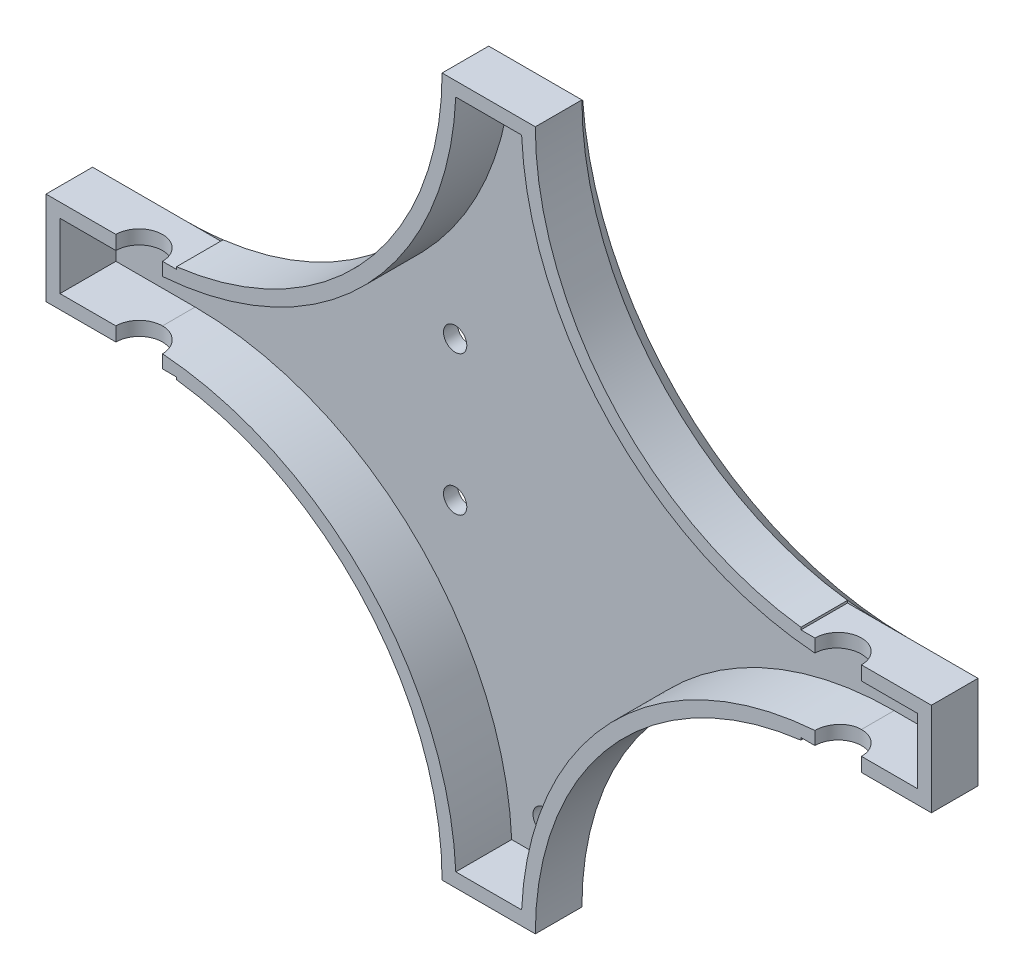
SolidWorks part; units mm, degrees
ref_plane "Front Plane" through (0, 0, 0) normal (0, 0, 1) x (1, 0, 0)
ref_plane "Top Plane" through (0, 0, 0) normal (0, 1, 0) x (1, 0, 0)
ref_plane "Right Plane" through (0, 0, 0) normal (1, 0, 0) x (0, 0, -1)
sketch "Sketch1" plane through (0, 0, 0) normal (0, 0, 1) x (1, 0, 0)
  line L1 (100, -75) -> (-100, -75)
  line L2 (100, -75) -> (100, 75)
  line L3 (100, 75) -> (-100, 75)
  line L4 (-100, -75) -> (-100, 75)
  line L5 (100, -75) -> (-100, 75) construction
  line L6 (100, 75) -> (-100, -75) construction
  point P0 (0, 0)
  dimension "D1" = 150
  dimension "D2" = 200
extrude "Boss-Extrude1" add sketch "Sketch1" along normal blind 15
sketch "Sketch2" plane through (0, 0, 0) normal (0, 0, -1) x (-1, 0, 0)
  line L0 (-100, 0) -> (100, 0)
  line L1 (0, 112.9215) -> (0, -139.2829) construction
  line L4 (-100, -75) -> (-100, 75) construction
  line L5 (100, 75) -> (100, -75) construction
sketch "Sketch5" plane through (0, 0, 0) normal (0, 0, -1) x (-1, 0, 0)
  line L0 (-100, 10) -> (106.2721, 10)
  line L1 (-100, -75) -> (-100, 75) construction
  line L2 (-15, -75) -> (5, -75)
  line L3 (-15, 75) -> (-15, -75)
  line L4 (-100, 0) -> (100, 0)
  line L5 (0, 10) -> (0, -10)
  line L6 (-65, -10) -> (101.6807, -10)
  line L7 (-65, -10) -> (-100, -10)
  line L8 (100, 75) -> (100, -75) construction
  line L9 (-100, 75) -> (100, 75) construction
  line L10 (100, -75) -> (-100, -75) construction
  line L11 (0, 112.9215) -> (0, -139.2829) construction
  line L12 (-15, 75) -> (5, 75)
  arc A3 (-80, 10) -> (-15, 75) centre (-80, 75) ccw
  arc A4 (-80, -10) -> (-15, -75) centre (-80, -75) cw
  arc A5 (5, 75) -> (70, 10) centre (70, 75) ccw
  arc A6 (5, -75) -> (70, -10) centre (70, -75) cw
  point P32 (70, -75)
  point P35 (70, -75)
  line M4 (100, -75) -> (100, 75)
  line M5 (100, 75) -> (-100, 75)
  line M6 (-100, 75) -> (-100, -75)
  line M7 (-100, -75) -> (100, -75)
  dimension "D2" = 15
  dimension "D3" = 130
  dimension "D4" = 130
  dimension "D5" = 100
  dimension "D6" = 85
extrude "Cut-Extrude2" cut sketch "Sketch5" against normal blind 30 contours A5 L0 M5 M4 | A6 L6 M7 M4 | A4 L7 M6 M7 | L0 A3 M5 M6
shell "Shell2" thickness 3
sketch "Sketch6" plane through (0, 0, 0) normal (0, 0, -1) x (-1, 0, 0)
  line L0 (-15, 75) -> (5, 75) construction
  line L1 (5, -75) -> (-15, -75) construction
  circle A0 centre (-5, 65) radius 2.5
  circle A1 centre (-5, -65) radius 2.5
  dimension "D1" = 5
  dimension "D2" = 5
  dimension "D3" = 10
  dimension "D4" = 10
extrude "Cut-Extrude3" cut sketch "Sketch6" against normal blind 30
sketch "Sketch7" plane through (0, 0, 0) normal (0, 1, 0) x (1, 0, 0)
  line L0 (-70, -15) -> (-100, -15) construction
  circle A0 centre (-80, -15) radius 5
  circle A1 centre (80, -15) radius 5
  dimension "D1" = 10
  dimension "D2" = 10
  dimension "D3" = 20
  dimension "D4" = 20
extrude "Cut-Extrude4" cut sketch "Sketch7" against normal blind 30 and the other way blind 30
chamfer "Chamfer1" distance 5 angle 45 12 edges at (-24.0381, 29.0381, 0) (-85, 10, 0) (-100, 0, 0) (-85, -10, 0) (90, -10, 0) (-24.0381, -29.0381, 0) (5, -75, 0) (34.0381, -29.0381, 0) (100, 0, 0) (90, 10, 0) (5, 75, 0) (34.0381, 29.0381, 0)
sketch "Sketch8" plane through (0, 0, 3) normal (0, 0, 1) x (1, 0, 0)
  line L0 (-24.8165, 0) -> (36.3426, 0) construction
  circle A0 centre (-22, 15) radius 2.5
  circle A1 centre (-22, -15) radius 2.5
  dimension "D1" = 5
  dimension "D2" = 15
  dimension "D3" = 22
extrude "Cut-Extrude5" cut sketch "Sketch8" against normal blind 10
sketch "Sketch9" plane through (0, 0, 0) normal (0, 0, 1) x (1, 0, 0)
  line L0 (15, 75) -> (-5, 75) construction
  line L1 (-5, -75) -> (15, -75) construction
  line L2 (5, 75) -> (5, -75)
  line L3 (5, -75) -> (-100, -75)
  line L4 (-100, -75) -> (-100, 75)
  line L5 (-100, 75) -> (5, 75)
extrude "Cut-Extrude8" cut sketch "Sketch9" along normal blind 50
mirror "Mirror4" about plane through (5, 75, 50) normal (-1, 0, 0) of bodies 113
sketch "Sketch10" plane through (0, 0, 0) normal (0, 0, 1) x (1, 0, 0)
  line L1 (-87, -7) -> (-87, 7) construction
  circle A0 centre (-14.2, 15) radius 2.5
  circle A1 centre (-14.2, -15) radius 2.5
  dimension "D1" = 5
  dimension "D2" = 5
  dimension "D3" = 72.8
  dimension "D5" = 30
  dimension "D6" = 15
extrude "Cut-Extrude9" cut sketch "Sketch10" along normal blind 50
sketch "Sketch11" plane through (-90, 0, 0) normal (-1, 0, 0) x (0, 0, 1)
  line L0 (15, 10.1926) -> (15, 75) construction
  line L1 (5, 10) -> (15, 10)
  line L2 (5, 10) -> (5, 12.8286)
  line L3 (5, 12.8286) -> (15, 12.8286)
  line L4 (15, 10) -> (15, 12.8286)
  line L5 (15, -75) -> (15, -10.1926) construction
  line L6 (5, -10) -> (15, -10)
  line L7 (5, -10) -> (5, -12.8286)
  line L8 (5, -12.8286) -> (15, -12.8286)
  line L9 (15, -10) -> (15, -12.8286)
extrude "Cut-Extrude10" cut sketch "Sketch11" against normal blind 28
sketch "Sketch12" plane through (100, 0, 0) normal (1, 0, 0) x (0, 0, -1)
  line L5 (-5, -75) -> (-5, -10) construction
  line L6 (-15, -10) -> (-5, -10)
  line L7 (-15, -10) -> (-15, -13.2868)
  line L8 (-15, -13.2868) -> (-5, -13.2868)
  line L9 (-5, -10) -> (-5, -13.2868)
  line L13 (-15, 75) -> (-15, 10.1926) construction
  line L14 (-5, 10) -> (-15, 10)
  line L15 (-5, 10) -> (-5, 13.4321)
  line L16 (-5, 13.4321) -> (-15, 13.4321)
  line L17 (-15, 10) -> (-15, 13.4321)
  dimension "D1" = 3.2868
extrude "Cut-Extrude11" cut sketch "Sketch12" against normal blind 28
